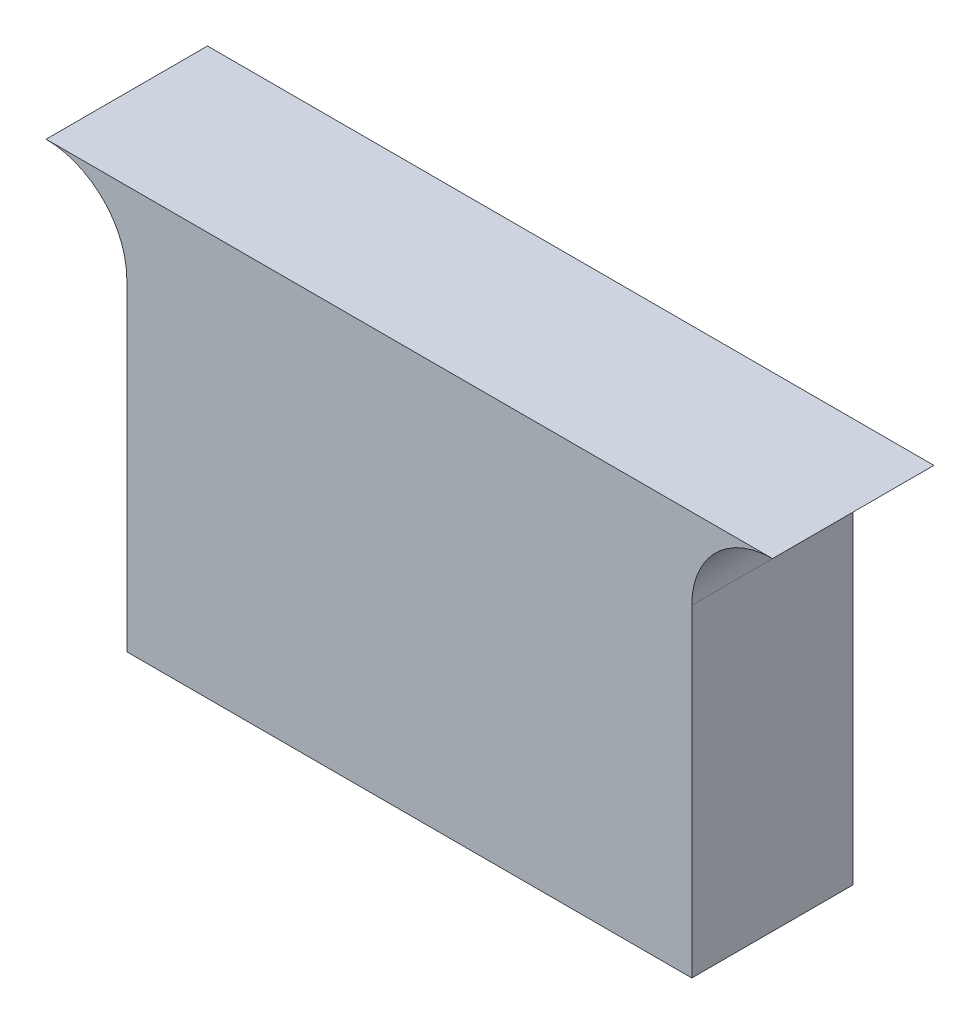
SolidWorks part; units mm, degrees
ref_plane "Alzado" through (0, 0, 0) normal (0, 0, 1) x (1, 0, 0)
ref_plane "Planta" through (0, 0, 0) normal (0, 1, 0) x (1, 0, 0)
ref_plane "Vista lateral" through (0, 0, 0) normal (1, 0, 0) x (0, 0, -1)
sketch "Croquis1" plane through (0, 0, 0) normal (0, 0, 1) x (1, 0, 0)
  line L0 (-16, 0) -> (-16, -8)
  line L1 (-2, 0) -> (-2, -8)
  line L2 (-2, -8) -> (-16, -8)
  line L3 (0, 2) -> (-18, 2)
  arc A0 (-18, 2) -> (-16, 0) centre (-18, 0) cw
  arc A1 (0, 2) -> (-2, 0) centre (0, 0) ccw
  dimension "D5" = 2
  dimension "D1" = 18
  dimension "D2" = 2
  dimension "D3" = 8
  dimension "D4" = 14
  dimension "D6" = 10
extrude "Saliente-Extruir2" add sketch "Croquis1" along normal blind 4 contours A0 L0 L2 L1 A1 L3
